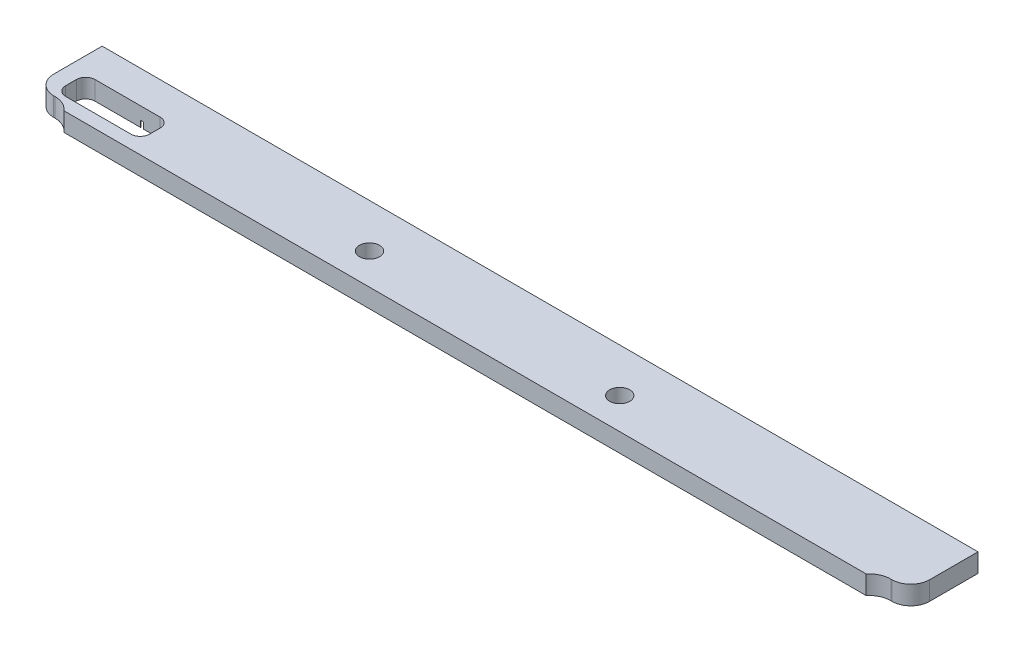
SolidWorks part; units mm, degrees
ref_plane "Front Plane" through (0, 0, 0) normal (0, 0, 1) x (1, 0, 0)
ref_plane "Top Plane" through (0, 0, 0) normal (0, 1, 0) x (1, 0, 0)
ref_plane "Right Plane" through (0, 0, 0) normal (1, 0, 0) x (0, 0, -1)
sketch "Sketch3" plane through (0, 0, 0) normal (0, 1, 0) x (1, 0, 0)
  line L6 (131.3747, -26.0938) -> (-8.6253, -26.0938)
  line L7 (-8.6253, -26.0938) -> (-8.6253, -33.8347)
  line L8 (-5.6253, -36.8347) -> (-5.431, -36.8347)
  line L9 (-2.7409, -38.0957) -> (125.4903, -38.0957)
  line L10 (128.1804, -36.8347) -> (128.3747, -36.8347)
  line L11 (131.3747, -33.8347) -> (131.3747, -26.0938)
  line L12 (131.3747, -26.0938) -> (-8.6253, -26.0938)
  line L13 (-8.6253, -26.0938) -> (-8.6253, -33.8347)
  line L14 (-5.6253, -36.8347) -> (-5.431, -36.8347)
  line L15 (-2.7409, -38.0957) -> (125.4903, -38.0957)
  line L16 (128.1804, -36.8347) -> (128.3747, -36.8347)
  line L17 (131.3747, -33.8347) -> (131.3747, -26.0938)
  arc A4 (-8.6253, -33.8347) -> (-5.6253, -36.8347) centre (-5.6253, -33.8347) ccw
  arc A5 (-2.7409, -38.0957) -> (-5.431, -36.8347) centre (-5.431, -40.3347) ccw
  arc A6 (128.1804, -36.8347) -> (125.4903, -38.0957) centre (128.1804, -40.3347) ccw
  arc A7 (128.3747, -36.8347) -> (131.3747, -33.8347) centre (128.3747, -33.8347) ccw
  arc A8 (-8.6253, -33.8347) -> (-5.6253, -36.8347) centre (-5.6253, -33.8347) ccw
  arc A9 (-2.7409, -38.0957) -> (-5.431, -36.8347) centre (-5.431, -40.3347) ccw
  arc A10 (128.1804, -36.8347) -> (125.4903, -38.0957) centre (128.1804, -40.3347) ccw
  arc A11 (128.3747, -36.8347) -> (131.3747, -33.8347) centre (128.3747, -33.8347) ccw
  dimension "D1" = 0
extrude "Boss-Extrude1" add sketch "Sketch3" along normal blind 3
sketch "Sketch4" plane through (0, 0, 0) normal (0, -1, 0) x (1, 0, 0)
  text T0 "2"
extrude "Cut-Extrude1" cut sketch "Sketch4" against normal blind 1
sketch "Sketch5" plane through (0, 3, 0) normal (0, 1, 0) x (1, 0, 0)
  line L0 (-4.5658, -35.9774) -> (5.8521, -35.9774)
  line L1 (7.3521, -34.4774) -> (7.3521, -32.7856)
  line L2 (5.8521, -31.2856) -> (-4.5658, -31.2856)
  line L3 (-6.0658, -32.7856) -> (-6.0658, -34.4774)
  line L4 (-4.5658, -35.4774) -> (5.8521, -35.4774)
  line L5 (-5.5658, -32.7856) -> (-5.5658, -34.4774)
  line L6 (5.8521, -31.7856) -> (-4.5658, -31.7856)
  line L7 (6.8521, -34.4774) -> (6.8521, -32.7856)
  line L8 (-4.5658, -35.4774) -> (5.8521, -35.4774)
  line L9 (-5.5658, -32.7856) -> (-5.5658, -34.4774)
  line L10 (5.8521, -31.7856) -> (-4.5658, -31.7856)
  line L11 (6.8521, -34.4774) -> (6.8521, -32.7856)
  arc A0 (5.8521, -35.9774) -> (7.3521, -34.4774) centre (5.8521, -34.4774) ccw
  arc A1 (7.3521, -32.7856) -> (5.8521, -31.2856) centre (5.8521, -32.7856) ccw
  arc A2 (-4.5658, -31.2856) -> (-6.0658, -32.7856) centre (-4.5658, -32.7856) ccw
  arc A3 (-6.0658, -34.4774) -> (-4.5658, -35.9774) centre (-4.5658, -34.4774) ccw
  arc A4 (-5.5658, -34.4774) -> (-4.5658, -35.4774) centre (-4.5658, -34.4774) ccw
  arc A5 (-4.5658, -31.7856) -> (-5.5658, -32.7856) centre (-4.5658, -32.7856) ccw
  arc A6 (6.8521, -32.7856) -> (5.8521, -31.7856) centre (5.8521, -32.7856) ccw
  arc A7 (5.8521, -35.4774) -> (6.8521, -34.4774) centre (5.8521, -34.4774) ccw
  arc A8 (-5.5658, -34.4774) -> (-4.5658, -35.4774) centre (-4.5658, -34.4774) ccw
  arc A9 (-4.5658, -31.7856) -> (-5.5658, -32.7856) centre (-4.5658, -32.7856) ccw
  arc A10 (6.8521, -32.7856) -> (5.8521, -31.7856) centre (5.8521, -32.7856) ccw
  arc A11 (5.8521, -35.4774) -> (6.8521, -34.4774) centre (5.8521, -34.4774) ccw
  dimension "D1" = 0
  dimension "D2" = 0.5
extrude "Cut-Extrude3" cut sketch "Sketch5" against normal up to next contours L3 A3 L0 A0 L1 A1 L2 A2
sketch "Sketch6" plane through (0, 3, 0) normal (0, 1, 0) x (1, 0, 0)
  arc A0 (41.1098, -31.4969) -> (41.1098, -34.6969) centre (41.1098, -33.0969) ccw construction
  arc A1 (41.1098, -34.6969) -> (41.1098, -31.4969) centre (41.1098, -33.0969) ccw construction
  arc A2 (41.1098, -31.4969) -> (41.1098, -34.6969) centre (41.1098, -33.0969) ccw
  arc A3 (41.1098, -34.6969) -> (41.1098, -31.4969) centre (41.1098, -33.0969) ccw
  arc A4 (81.1098, -31.4969) -> (81.1098, -34.6969) centre (81.1098, -33.0969) ccw construction
  arc A5 (81.1098, -34.6969) -> (81.1098, -31.4969) centre (81.1098, -33.0969) ccw construction
  arc A6 (81.1098, -31.4969) -> (81.1098, -34.6969) centre (81.1098, -33.0969) ccw
  arc A7 (81.1098, -34.6969) -> (81.1098, -31.4969) centre (81.1098, -33.0969) ccw
extrude "Cut-Extrude4" cut sketch "Sketch6" against normal up to next
